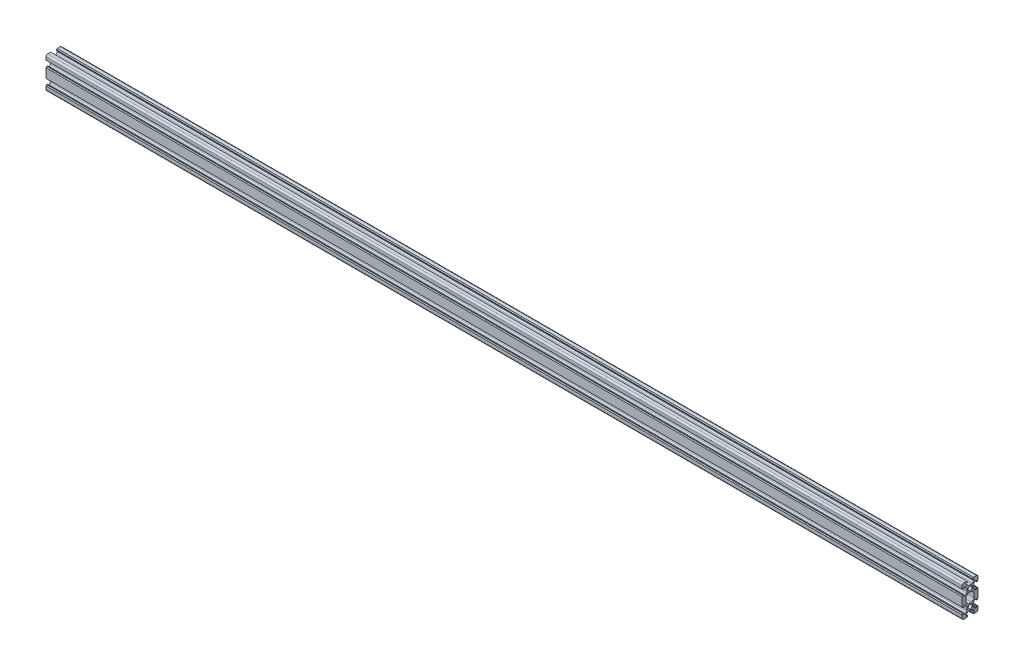
SolidWorks part; units mm, degrees
ref_plane "Front Plane" through (0, 0, 0) normal (0, 0, 1) x (1, 0, 0)
ref_plane "Top Plane" through (0, 0, 0) normal (0, 1, 0) x (1, 0, 0)
ref_plane "Right Plane" through (0, 0, 0) normal (1, 0, 0) x (0, 0, -1)
sketch "Sketch1" plane through (0, 0, 0) normal (1, 0, 0) x (0, 0, -1)
  line B0 (6.9, 38) -> (5, 38)
  line B1 (19, 6.9) -> (20, 5.9)
  line B2 (14.4142, 15.8284) -> (13.1236, 14.5379)
  line B3 (20, 14.1) -> (19, 13.1)
  line B4 (15.8284, 5.5858) -> (14.5379, 6.8764)
  line B5 (17.2426, 5) -> (18, 5)
  line B6 (18, 6.9) -> (18, 5)
  line B7 (17.2426, 15) -> (18, 15)
  line B8 (8.2906, 13.9521) -> (11.7094, 13.9521)
  line B9 (18, 15) -> (18, 13.1)
  line B10 (18, 13.1) -> (19, 13.1)
  line B11 (18, 6.9) -> (19, 6.9)
  line B12 (13.9521, 11.7094) -> (13.9521, 8.2906)
  line B13 (6.8764, 14.5379) -> (5.5858, 15.8284)
  line B14 (20, 5.9) -> (20, 2)
  line B15 (14.5379, 13.1236) -> (15.8284, 14.4142)
  line B16 (6.9, 1) -> (5.9, 0)
  line B17 (18, 0) -> (14.1, 0)
  line B18 (14.1, 0) -> (13.1, 1)
  line B19 (5.5858, 4.1716) -> (6.8764, 5.4621)
  line B20 (5, 2.7574) -> (5, 2)
  line B21 (6.9, 2) -> (5, 2)
  line B22 (15, 2.7574) -> (15, 2)
  line B23 (15, 2) -> (13.1, 2)
  line B24 (13.1, 2) -> (13.1, 1)
  line B25 (6.9, 2) -> (6.9, 1)
  line B26 (11.7094, 6.0479) -> (8.2906, 6.0479)
  line B27 (5.9, 0) -> (2, 0)
  line B28 (13.1236, 5.4621) -> (14.4142, 4.1716)
  line B29 (1, 13.1) -> (0, 14.1)
  line B30 (0, 2) -> (0, 5.9)
  line B31 (0, 5.9) -> (1, 6.9)
  line B32 (4.1716, 14.4142) -> (5.4621, 13.1236)
  line B33 (2.7574, 15) -> (2, 15)
  line B34 (2, 13.1) -> (2, 15)
  line B35 (2.7574, 5) -> (2, 5)
  line B36 (2, 5) -> (2, 6.9)
  line B37 (2, 6.9) -> (1, 6.9)
  line B38 (2, 13.1) -> (1, 13.1)
  line B39 (6.0479, 8.2906) -> (6.0479, 11.7094)
  line B40 (5.4621, 6.8764) -> (4.1716, 5.5858)
  line B41 (19, 26.9) -> (20, 25.9)
  line B42 (15, 38) -> (13.1, 38)
  line B43 (14.1, 40) -> (13.1, 39)
  line B44 (14.4142, 35.8284) -> (13.1236, 34.5379)
  line B45 (18, 35) -> (18, 33.1)
  line B46 (6.9, 38) -> (6.9, 39)
  line B47 (18, 40) -> (14.1, 40)
  line B48 (5.9, 40) -> (2, 40)
  line B49 (0, 25.9) -> (1, 26.9)
  line B50 (17.2426, 25) -> (18, 25)
  line B51 (5, 37.2426) -> (5, 38)
  line B52 (18, 26.9) -> (19, 26.9)
  line B53 (13.1, 38) -> (13.1, 39)
  line B54 (2, 26.9) -> (1, 26.9)
  line B55 (20, 34.1) -> (19, 33.1)
  line B56 (5, 22.7574) -> (5, 17.2426)
  line B57 (20, 34.1) -> (20, 38)
  line B58 (0, 38) -> (0, 34.1)
  line B59 (13.1236, 25.4621) -> (14.4142, 24.1716)
  line B60 (2, 25) -> (2, 26.9)
  line B61 (6.0479, 28.2906) -> (6.0479, 31.7094)
  line B62 (18, 33.1) -> (19, 33.1)
  line B63 (15, 37.2426) -> (15, 38)
  line B64 (2, 33.1) -> (2, 35)
  line B65 (18, 26.9) -> (18, 25)
  line B66 (11.7094, 26.0479) -> (8.2906, 26.0479)
  line B67 (17.2426, 35) -> (18, 35)
  line B68 (20, 25.9) -> (20, 14.1)
  line B69 (1, 33.1) -> (0, 34.1)
  line B70 (14.5379, 33.1236) -> (15.8284, 34.4142)
  line B71 (4.1716, 34.4142) -> (5.4621, 33.1236)
  line B72 (13.9521, 31.7094) -> (13.9521, 28.2906)
  line B73 (2.7574, 35) -> (2, 35)
  line B74 (8.2906, 33.9521) -> (11.7094, 33.9521)
  line B75 (6.9, 39) -> (5.9, 40)
  line B76 (5.4621, 26.8764) -> (4.1716, 25.5858)
  line B77 (0, 14.1) -> (0, 25.9)
  line B78 (5.5858, 24.1716) -> (6.8764, 25.4621)
  line B79 (15.8284, 25.5858) -> (14.5379, 26.8764)
  line B80 (6.8764, 34.5379) -> (5.5858, 35.8284)
  line B81 (15, 22.7574) -> (15, 17.2426)
  line B82 (2.7574, 25) -> (2, 25)
  line B83 (2, 33.1) -> (1, 33.1)
  circle B84 centre (10, 10) radius 2.5
  arc B85 (5.4621, 13.1236) -> (6.0479, 11.7094) centre (4.0479, 11.7094) cw
  arc B86 (4.1716, 14.4142) -> (2.7574, 15) centre (2.7574, 13) ccw
  arc B87 (5, 17.2426) -> (5.5858, 15.8284) centre (7, 17.2426) ccw
  arc B88 (15, 17.2426) -> (14.4142, 15.8284) centre (13, 17.2426) cw
  arc B89 (17.2426, 15) -> (15.8284, 14.4142) centre (17.2426, 13) ccw
  arc B90 (15.8284, 5.5858) -> (17.2426, 5) centre (17.2426, 7) ccw
  arc B91 (15, 2.7574) -> (14.4142, 4.1716) centre (13, 2.7574) ccw
  arc B92 (5.5858, 4.1716) -> (5, 2.7574) centre (7, 2.7574) ccw
  arc B93 (2.7574, 5) -> (4.1716, 5.5858) centre (2.7574, 7) ccw
  arc B94 (6.0479, 8.2906) -> (5.4621, 6.8764) centre (4.0479, 8.2906) cw
  arc B95 (6.8764, 5.4621) -> (8.2906, 6.0479) centre (8.2906, 4.0479) cw
  arc B96 (11.7094, 6.0479) -> (13.1236, 5.4621) centre (11.7094, 4.0479) cw
  arc B97 (14.5379, 6.8764) -> (13.9521, 8.2906) centre (15.9521, 8.2906) cw
  arc B98 (13.9521, 11.7094) -> (14.5379, 13.1236) centre (15.9521, 11.7094) cw
  arc B99 (11.7094, 13.9521) -> (13.1236, 14.5379) centre (11.7094, 15.9521) ccw
  arc B100 (8.2906, 13.9521) -> (6.8764, 14.5379) centre (8.2906, 15.9521) cw
  arc B101 (2, 0) -> (0, 2) centre (2, 2) cw
  arc B102 (20, 2) -> (18, 0) centre (18, 2) cw
  arc B103 (11.7094, 26.0479) -> (13.1236, 25.4621) centre (11.7094, 24.0479) cw
  arc B104 (13.9521, 31.7094) -> (14.5379, 33.1236) centre (15.9521, 31.7094) cw
  arc B105 (14.5379, 26.8764) -> (13.9521, 28.2906) centre (15.9521, 28.2906) cw
  arc B106 (5.5858, 24.1716) -> (5, 22.7574) centre (7, 22.7574) ccw
  arc B107 (5, 37.2426) -> (5.5858, 35.8284) centre (7, 37.2426) ccw
  arc B108 (11.7094, 33.9521) -> (13.1236, 34.5379) centre (11.7094, 35.9521) ccw
  arc B109 (15, 22.7574) -> (14.4142, 24.1716) centre (13, 22.7574) ccw
  arc B110 (2.7574, 25) -> (4.1716, 25.5858) centre (2.7574, 27) ccw
  arc B111 (15, 37.2426) -> (14.4142, 35.8284) centre (13, 37.2426) cw
  circle B112 centre (10, 30) radius 2.5
  arc B113 (8.2906, 33.9521) -> (6.8764, 34.5379) centre (8.2906, 35.9521) cw
  arc B114 (6.0479, 28.2906) -> (5.4621, 26.8764) centre (4.0479, 28.2906) cw
  arc B115 (6.8764, 25.4621) -> (8.2906, 26.0479) centre (8.2906, 24.0479) cw
  arc B116 (4.1716, 34.4142) -> (2.7574, 35) centre (2.7574, 33) ccw
  arc B117 (15.8284, 25.5858) -> (17.2426, 25) centre (17.2426, 27) ccw
  arc B118 (5.4621, 33.1236) -> (6.0479, 31.7094) centre (4.0479, 31.7094) cw
  arc B119 (2, 40) -> (0, 38) centre (2, 38) ccw
  arc B120 (17.2426, 35) -> (15.8284, 34.4142) centre (17.2426, 33) ccw
  arc B121 (20, 38) -> (18, 40) centre (18, 38) ccw
sketch_block_instance "2040-1"
sketch_block "2040" parameters "D1"=2, "D2"=2
extrude "Boss-Extrude1" add sketch "Sketch1" along normal blind 1160
sketch "Sketch2" plane through (0, 0, 0) normal (0, 0, 1) x (1, 0, 0)
  line L0 (30, 38) -> (550, 38)
  line L1 (30, 40) -> (30, 38)
  line L2 (30, 40) -> (550, 40)
  line L3 (550, 40) -> (550, 38)
  line L4 (580, 40) -> (580, 93.5046) construction
  line L5 (1160, 40) -> (0, 40) construction
  line L6 (610, 40) -> (610, 38)
  line L7 (1130, 40) -> (610, 40)
  line L8 (1130, 40) -> (1130, 38)
  line L9 (1130, 38) -> (610, 38)
  point P8 (290, 40)
  point P9 (870, 40)
  dimension "D1" = 2
